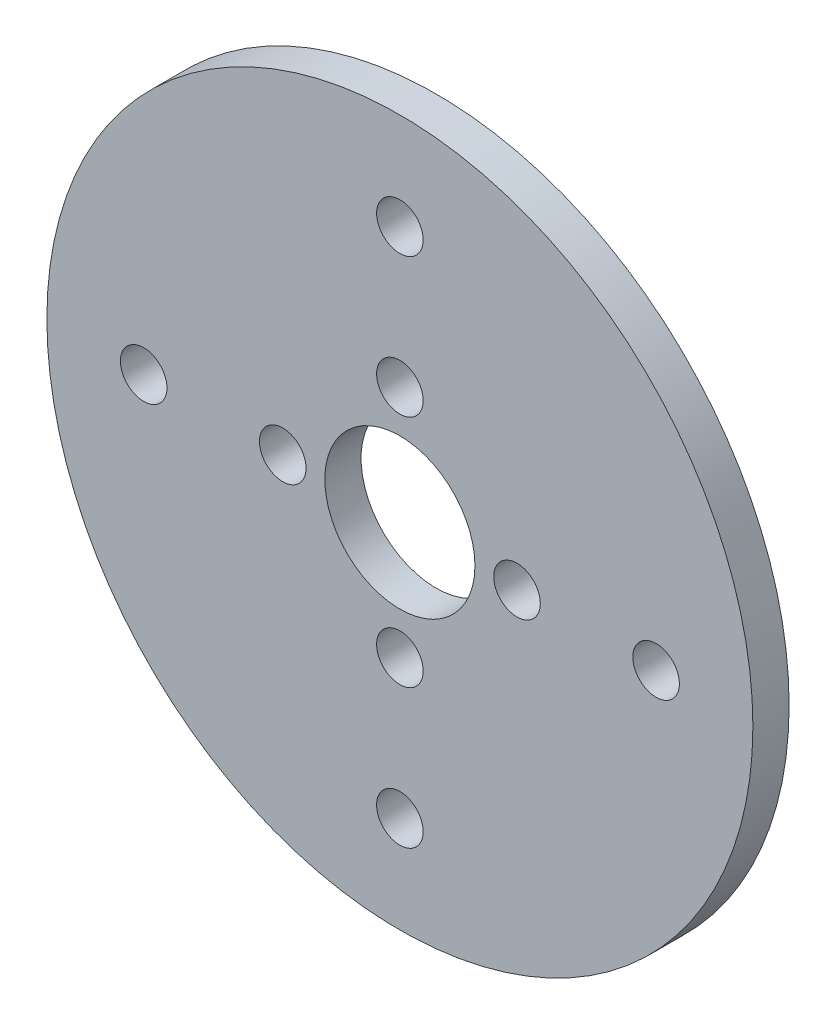
SolidWorks part; units mm, degrees
ref_plane "Front Plane" through (0, 0, 0) normal (0, 0, 1) x (1, 0, 0)
ref_plane "Top Plane" through (0, 0, 0) normal (0, 1, 0) x (1, 0, 0)
ref_plane "Right Plane" through (0, 0, 0) normal (1, 0, 0) x (0, 0, -1)
sketch "Sketch1" plane through (0, 0, 0) normal (0, 0, 1) x (1, 0, 0)
  circle A0 centre (0, 0) radius 34.1
  dimension "D1" = 68.2
extrude "Boss-Extrude1" add sketch "Sketch1" along normal mid plane 3.5
sketch "Sketch3" plane through (0, 0, 1.75) normal (0, 0, 1) x (1, 0, 0)
  line L0 (0, 0) -> (0, 24.75) construction
  circle A0 centre (0, 24.75) radius 2.25
  circle A8 centre (0, 0) radius 11.3137 construction
  circle A9 centre (0, 11.3137) radius 2.25
  circle A10 centre (24.75, 0) radius 2.25
  circle A11 centre (11.3137, 0) radius 2.25
  circle A12 centre (0, -24.75) radius 2.25
  circle A13 centre (0, -11.3137) radius 2.25
  circle A14 centre (-24.75, 0) radius 2.25
  circle A15 centre (-11.3137, 0) radius 2.25
  point P6 (-3.2356, -10.7207)
  point P7 (0, 0)
  point P21 (0, 0)
  dimension "D2" = 4.5
  dimension "D3" = 22.6274
  dimension "D4" = 4.5
  dimension "D5" = 4
  dimension "D1" = 24.75
extrude "Cut-Extrude2" cut sketch "Sketch3" against normal through all
sketch "Sketch2" plane through (0, 0, 1.75) normal (0, 0, 1) x (1, 0, 0)
  circle A0 centre (0, 0) radius 7.25
  dimension "D1" = 14.5
extrude "Cut-Extrude1" cut sketch "Sketch2" against normal through all
